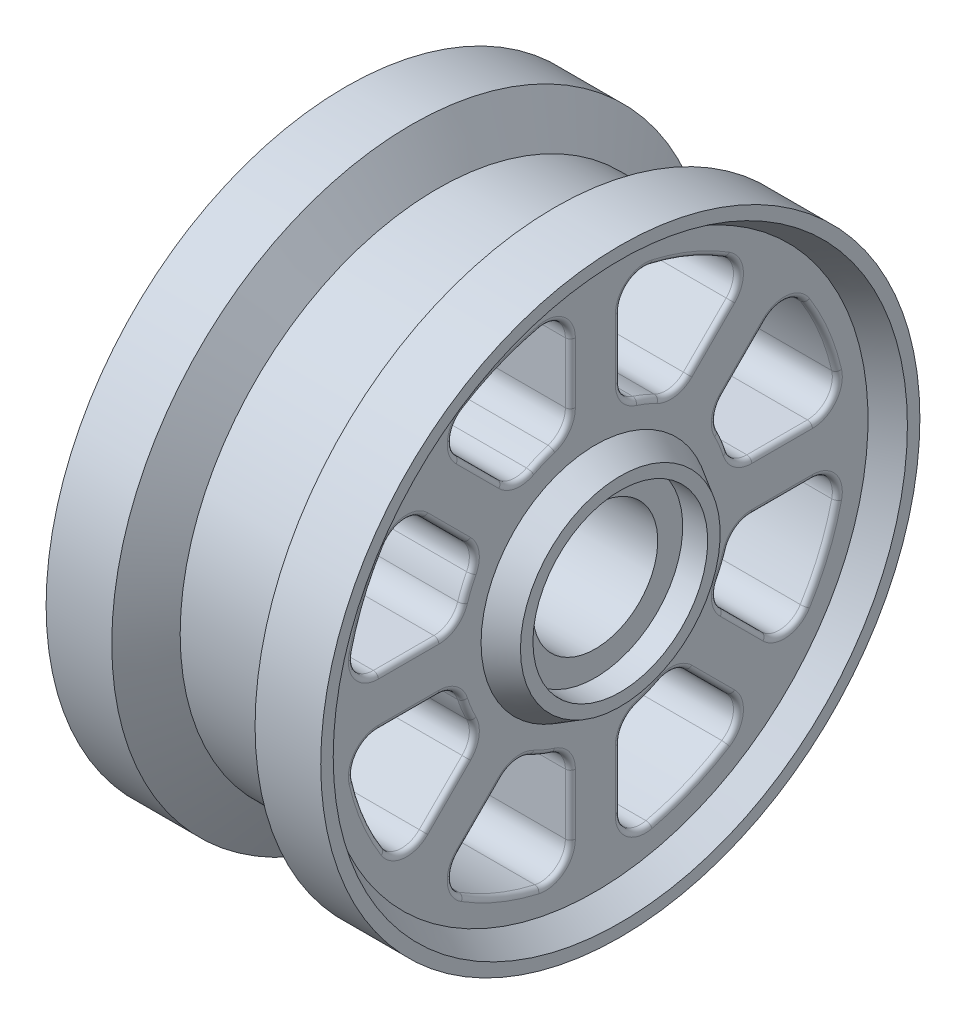
SolidWorks part; units mm, degrees
material "ABS"
ref_plane "Front" through (0, 0, 0) normal (0, 0, 1) x (1, 0, 0)
ref_plane "Top" through (0, 0, 0) normal (0, 1, 0) x (1, 0, 0)
ref_plane "Right" through (0, 0, 0) normal (1, 0, 0) x (0, 0, -1)
sketch "Sketch1" plane through (0, 0, 0) normal (0, 0, 1) x (1, 0, 0)
  line L0 (0, 0) -> (40.2325, 0) construction
  line L1 (0, 0) -> (0, 28.3421) construction
  line L2 (-0.915, 5.15) -> (0.915, 5.15)
  line L3 (0.915, 5.15) -> (1.435, 6)
  line L4 (1.435, 6) -> (2.75, 6)
  line L5 (2.75, 6) -> (2.75, 5.75)
  line L6 (2.75, 5.75) -> (2.25, 5.4613)
  line L7 (2.25, 5.4613) -> (2.25, 2.2887)
  line L9 (2.25, 2.2887) -> (2.75, 2)
  line L10 (2.75, 2) -> (2.75, 1.75)
  line L11 (2.75, 1.75) -> (2.25, 1.75)
  line L12 (2.25, 1.75) -> (2.25, 1.25)
  line L13 (2.25, 1.25) -> (-2.25, 1.25)
  line L14 (-2.25, 1.75) -> (-2.25, 1.25)
  line L15 (-2.75, 1.75) -> (-2.25, 1.75)
  line L16 (-2.75, 2) -> (-2.75, 1.75)
  line L17 (-2.25, 2.2887) -> (-2.75, 2)
  line L18 (-2.25, 5.4613) -> (-2.25, 2.2887)
  line L19 (-2.75, 5.75) -> (-2.25, 5.4613)
  line L20 (-2.75, 6) -> (-2.75, 5.75)
  line L21 (-1.435, 6) -> (-2.75, 6)
  line L22 (-0.915, 5.15) -> (-1.435, 6)
  point P19 (2.25, 1.5)
  point P25 (0, 1.25)
  point P34 (0, 5.15)
  dimension "D1" = 1.83
  dimension "D2" = 2.87
  dimension "D3" = 5.5
  dimension "D4" = 10.3
  dimension "D5" = 12
  dimension "D6" = 30
  dimension "D7" = 0.5
  dimension "D8" = 2.5
  dimension "D9" = 0.25
  dimension "D10" = 60
  dimension "D11" = 0.5
  dimension "D12" = 0.25
revolve "Revolve1" add sketch "Sketch1" angle 360 about L0
sketch "Sketch2" plane through (2.25, 0, 0) normal (1, 0, 0) x (0, 0, -1)
  line L0 (2.5696, 1.8625) -> (3.427, 2.7198)
  line L1 (0, 0) -> (0, 7.759) construction
  line L2 (3.134, 0.5) -> (4.3464, 0.5)
  line L3 (0, 0) -> (9.3708, 0) construction
  line L4 (0, 0) -> (7.0286, 7.0286) construction
  arc A4 (4.8337, 1.1121) -> (4.2043, 2.6316) centre (0, 0) ccw
  arc A5 (2.6577, 0.848) -> (2.4789, 1.2796) centre (0, 0) ccw
  arc A6 (2.6577, 0.848) -> (3.134, 0.5) centre (3.134, 1) ccw
  arc A7 (4.3464, 0.5) -> (4.8337, 1.1121) centre (4.3464, 1) ccw
  arc A8 (3.427, 2.7198) -> (4.2043, 2.6316) centre (3.7805, 2.3663) cw
  arc A9 (2.5696, 1.8625) -> (2.4789, 1.2796) centre (2.9232, 1.509) ccw
  circle A10 centre (0, 0) radius 2.2887 construction
  dimension "D1" = 4.96
  dimension "D2" = 2.7897
  dimension "D5" = 0.5
  dimension "D6" = 45
  dimension "D3" = 0.5
  dimension "D4" = 0.5
extrude "Cut-Extrude1" cut sketch "Sketch2" against normal up to surface (4.5 mm away) up to face at (-2.25, 0, 2.2887)
pattern_circular "CirPattern1" count 8 over 360 about axis through (0, 0, 0) along (1, 0, 0) of "Cut-Extrude1"
fillet "Fillet1" radius 0.1 119 edges at (2.25, 1.8981, -4.5824) (2.25, 2.8631, -3.8369) (2.25, 2.2912, -2.9983) (2.25, 1.5859, -2.4291) (2.25, 1.0676, -2.5773) (2.25, 0.5963, -2.839) (2.25, 0.5, -3.7402) (2.25, 3.8369, -2.8631) (2.25, 4.5824, -1.8981) (2.25, 4.7376, -0.6886) (2.25, 3.7402, -0.5) (2.25, 2.839, -0.5963) (2.25, 2.5773, -1.0676) (2.25, 2.4291, -1.5859) (2.25, 2.9983, -2.2912) (2.25, 2.8631, 3.8369) (2.25, 1.8981, 4.5824) (2.25, 0.6886, 4.7376) (2.25, 0.5, 3.7402) (2.25, 0.5963, 2.839) (2.25, 1.0676, 2.5773) (2.25, 1.5859, 2.4291) (2.25, 2.2912, 2.9983) (2.25, 4.7376, 0.6886) (2.25, 4.5824, 1.8981) (2.25, 3.8369, 2.8631) (2.25, 2.9983, 2.2912) (2.25, 2.5773, 1.0676) (2.25, 2.839, 0.5963) (2.25, 3.7402, 0.5) (-2.25, 1.5859, -2.4291) (-2.25, 2.2912, -2.9983) (-2.25, 2.8631, -3.8369) (-2.25, 1.8981, -4.5824) (-2.25, 0.6886, -4.7376) (-2.25, 0.5, -3.7402) (-2.25, 0.5963, -2.839) (-2.25, 1.0676, -2.5773) (-2.25, -0.5963, -2.839) (-2.25, -0.5, -3.7402) (-2.25, -0.6886, -4.7376) (-2.25, -1.8981, -4.5824) (-2.25, -2.8631, -3.8369) (-2.25, -2.2912, -2.9983) (-2.25, -1.5859, -2.4291) (-2.25, -1.0676, -2.5773) (-2.25, 2.839, -0.5963) (-2.25, 3.7402, -0.5) (-2.25, 4.7376, -0.6886) (-2.25, 4.5824, -1.8981) (-2.25, 3.8369, -2.8631) (-2.25, 2.9983, -2.2912) (-2.25, 2.4291, -1.5859) (-2.25, 2.4291, 1.5859) (-2.25, 3.8369, 2.8631) (-2.25, 4.5824, 1.8981) (-2.25, 4.7376, 0.6886) (-2.25, 3.7402, 0.5) (-2.25, 2.839, 0.5963) (-2.25, 2.5773, 1.0676) (-2.25, -2.4291, -1.5859) (-2.25, -2.9983, -2.2912) (-2.25, -4.5824, -1.8981) (-2.25, -4.7376, -0.6886) (-2.25, -3.7402, -0.5) (-2.25, -2.839, -0.5963) (-2.25, -2.5773, -1.0676) (-2.25, -2.839, 0.5963) (-2.25, -4.5824, 1.8981) (-2.25, -3.8369, 2.8631) (-2.25, -2.9983, 2.2912) (-2.25, -2.4291, 1.5859) (-2.25, -2.5773, 1.0676) (-2.25, -1.5859, 2.4291) (-2.25, -2.2912, 2.9983) (-2.25, -2.8631, 3.8369) (-2.25, -1.8981, 4.5824) (-2.25, -0.5, 3.7402) (-2.25, -0.5963, 2.839) (-2.25, -1.0676, 2.5773) (-2.25, 0.5963, 2.839) (-2.25, 0.5, 3.7402) (-2.25, 0.6886, 4.7376) (-2.25, 1.8981, 4.5824) (-2.25, 2.8631, 3.8369) (-2.25, 2.2912, 2.9983) (-2.25, 1.5859, 2.4291) (-2.25, 1.0676, 2.5773) (2.25, -2.8631, -3.8369) (2.25, -2.2912, -2.9983) (2.25, -1.5859, -2.4291) (2.25, -1.0676, -2.5773) (2.25, -0.5963, -2.839) (2.25, -0.5, -3.7402) (2.25, -4.5824, -1.8981) (2.25, -4.7376, -0.6886) (2.25, -3.7402, -0.5) (2.25, -2.839, -0.5963) (2.25, -2.5773, -1.0676) (2.25, -2.4291, -1.5859) (2.25, -2.9983, -2.2912) (2.25, -4.5824, 1.8981) (2.25, -3.8369, 2.8631) (2.25, -2.9983, 2.2912) (2.25, -2.4291, 1.5859) (2.25, -2.5773, 1.0676) (2.25, -2.839, 0.5963) (2.25, -3.7402, 0.5) (2.25, -1.0676, 2.5773) (2.25, -1.5859, 2.4291) (2.25, -2.2912, 2.9983) (2.25, -2.8631, 3.8369) (2.25, -1.8981, 4.5824) (2.25, -0.6886, 4.7376) (2.25, -0.5, 3.7402) (2.25, -0.6886, -4.7376) (2.25, -3.8369, -2.8631) (2.25, -4.7376, 0.6886) (2.25, -0.5963, 2.839)
